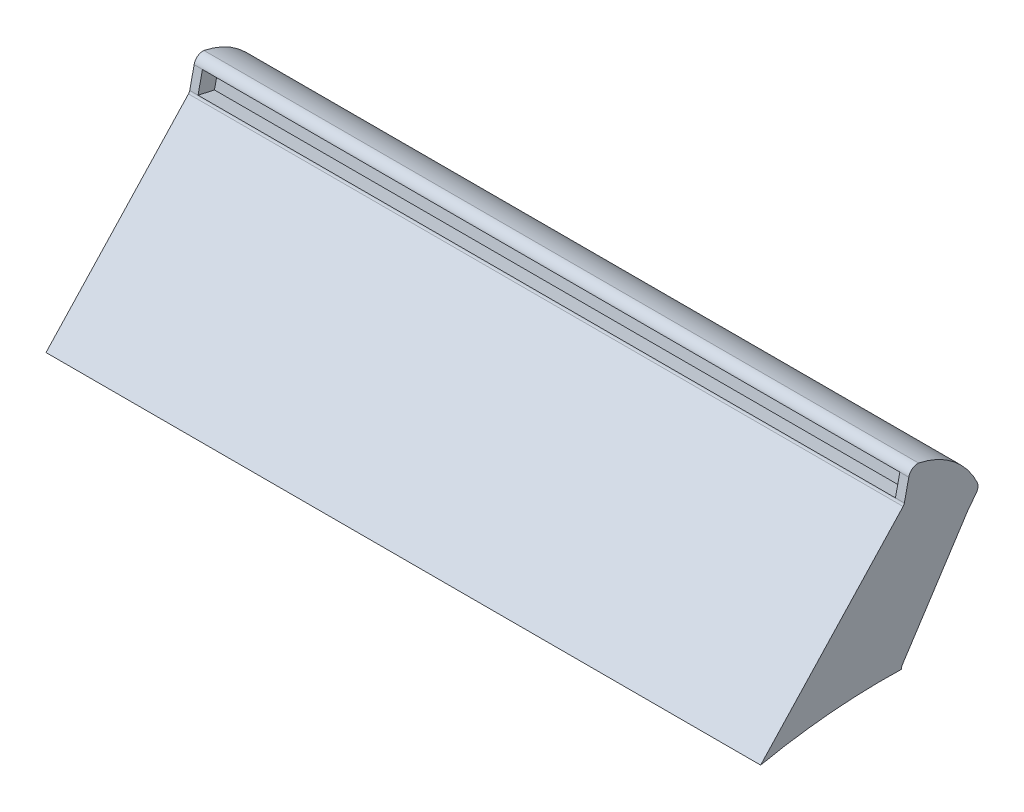
SolidWorks part; units mm, degrees
ref_plane "Front Plane" through (0, 0, 0) normal (0, 0, 1) x (1, 0, 0)
ref_plane "Top Plane" through (0, 0, 0) normal (0, 1, 0) x (1, 0, 0)
ref_plane "Right Plane" through (0, 0, 0) normal (1, 0, 0) x (0, 0, -1)
sketch "Sketch1" plane through (0, 0, 0) normal (1, 0, 0) x (0, 0, -1)
  line L0 (-147.7406, -92.809) -> (21.7379, 88.8759)
  line L1 (23.2081, 91.6694) -> (28.4702, 115.6184)
  line L2 (109.3386, 59.9079) -> (99.4589, 47.4132)
  line L3 (99.4589, 47.4132) -> (20.9292, -73.5119)
  arc A0 (28.4702, 115.6184) -> (40.0945, 124.4276) centre (39.0904, 113.6783) cw
  arc A1 (40.0945, 124.4276) -> (109.9794, 69.5374) centre (19.9145, 26.802) cw
  arc A2 (109.9794, 69.5374) -> (109.3386, 59.9079) centre (100.0151, 65.3643) cw
  arc A3 (20.9292, -73.5119) -> (19.6386, -77.869) centre (27.6386, -77.869) ccw
  arc A4 (19.6386, -77.869) -> (-147.7406, -92.809) centre (-0.4093, -798.3418) ccw
  spline S0 degree 2 poles (21.7379, 88.8759) (22.8464, 90.0745) (23.2081, 91.6694) knots 0 0 0 1 1 1
  dimension "D1" = 99.6894
  dimension "D2" = 10.796
  dimension "D3" = 10.8028
  dimension "D8" = 720.7517
  dimension "D9" = 8
  dimension "D4" = 15.9288
  dimension "D5" = 144.1866
  dimension "D6" = 248.46
  dimension "D7" = 24.5203
  dimension "D10" = 10.009
extrude "Boss-Extrude1" add sketch "Sketch1" along normal blind 850
sketch "Sketch2" plane through (0, -0.6428, -2.9255) normal (0, 0.2146, 0.9767) x (1, 0, 0)
  line L0 (850, 94.5141) -> (0, 94.5141) construction
  line L1 (9.8771, 94.5141) -> (839.3803, 94.5141)
  line L2 (9.8771, 94.5141) -> (9.8771, 119.0344)
  line L3 (9.8771, 119.0344) -> (839.3803, 119.0344)
  line L4 (839.3803, 94.5141) -> (839.3803, 119.0344)
  line L5 (850, 119.0344) -> (0, 119.0344) construction
extrude "Cut-Extrude1" cut sketch "Sketch2" against normal blind 20
